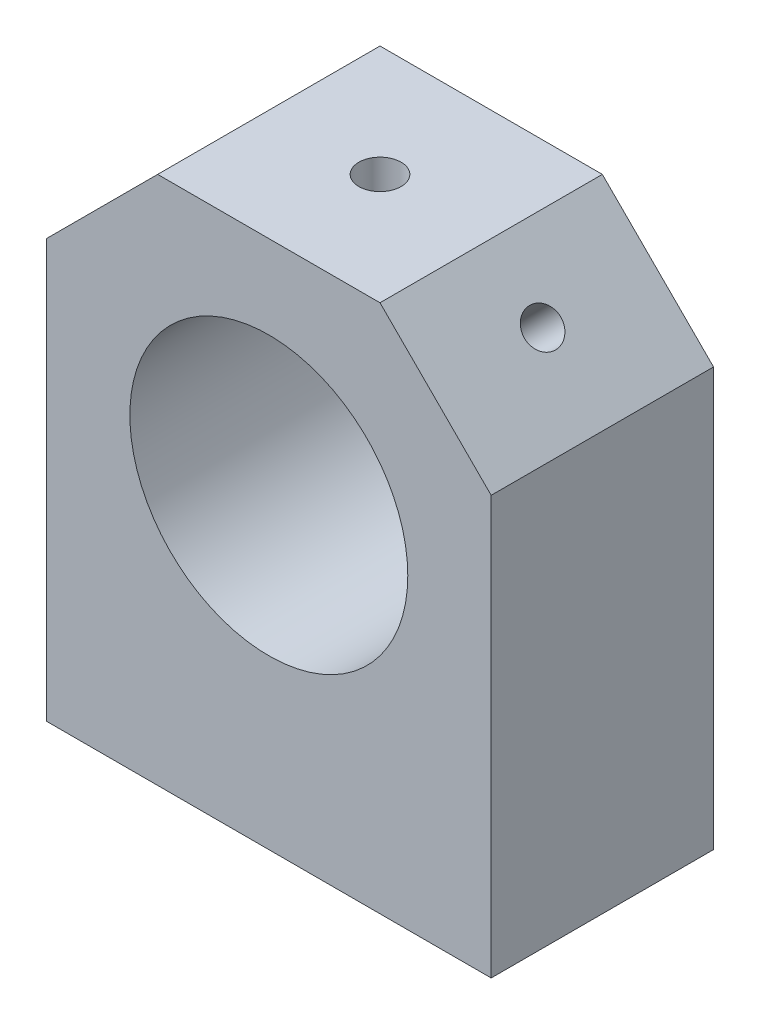
SolidWorks part; units mm, degrees
ref_plane "Front Plane" through (0, 0, 0) normal (0, 0, 1) x (1, 0, 0)
ref_plane "Top Plane" through (0, 0, 0) normal (0, 1, 0) x (1, 0, 0)
ref_plane "Right Plane" through (0, 0, 0) normal (1, 0, 0) x (0, 0, -1)
sketch "Sketch2" plane through (0, 0, 0) normal (0, 0, 1) x (1, 0, 0)
  line L0 (-38.1, 60.452) -> (-50.8, 47.752)
  line L1 (0, 0) -> (-50.8, 0)
  line L2 (0, 0) -> (0, 47.752)
  line L3 (-12.7, 60.452) -> (-38.1, 60.452)
  line L4 (-50.8, 0) -> (-50.8, 47.752)
  line L5 (-12.7, 60.452) -> (0, 47.752)
  circle A0 centre (-25.4, 35.052) radius 15.875
  dimension "D8" = 31.75
  dimension "D1" = 50.8
  dimension "D2" = 60.452
  dimension "D3" = 25.4
  dimension "D4" = 45
  dimension "D5" = 45
  dimension "D6" = 25.4
  dimension "D7" = 35.052
extrude "Boss-Extrude1" add sketch "Sketch2" along normal blind 25.4
sketch "Sketch3" plane through (-49.276, 49.276, 0) normal (-0.7071, 0.7071, 0) x (0, 0, 1)
  line L0 (25.4, 15.8053) -> (0, 15.8053) construction
  line L1 (25.4, 15.8053) -> (25.4, -2.1553) construction
  circle A0 centre (12.7, 6.1533) radius 2.0828
  dimension "D3" = 4.1656
  dimension "D1" = 9.652
  dimension "D2" = 12.7
sketch "Sketch4" plane through (0, 60.452, 0) normal (0, 1, 0) x (1, 0, 0)
  line L0 (-12.7, -25.4) -> (-12.7, 0) construction
  line L1 (-12.7, -25.4) -> (-38.1, -25.4) construction
  circle A0 centre (-25.4, -12.7) radius 2.413
  dimension "D3" = 4.826
  dimension "D1" = 12.7
  dimension "D2" = 12.7
hole_wizard "1/2-20 Tapped Hole1" positions "3DSketch2" profile "Sketch7" tap size "1/2-20" standard "ANSI Inch"
sketch3d "3DSketch2"
  point P0 (-25.4, 60.452, 12.7)
sketch "Sketch7" plane through (-25.4, 60.452, 12.7) normal (1, 0, 0) x (0, 0, 1)
  line L0 (0, 0) -> (0, 33.1999)
  line L1 (0, 33.1999) -> (2.413, 31.75)
  line L2 (2.413, 31.75) -> (2.413, 0)
  line L5 (2.413, 0) -> (0, 0)
  line L10 (0, 33.1999) -> (-2.413, 31.75) construction
  line L11 (0, -6.35) -> (0, 107.95) construction
  dimension "Tap Drill Dia." = 4.826
  dimension "Tap Drill Depth" = 31.75
  dimension "Drill Angle" = 118
cosmetic thread "Hole Thread1" parameters "D1"=25.4, "D2"=12.7
hole_wizard "1/2-20 Tapped Hole2" positions "3DSketch3" profile "Sketch8" tap size "1/2-20" standard "ANSI Inch"
sketch3d "3DSketch3"
  point P0 (-44.925, 53.627, 12.7)
sketch "Sketch8" plane through (-44.925, 53.627, 12.7) normal (0, 0, 1) x (-0.7071, -0.7071, 0)
  line L0 (0, 0) -> (0, 33.0015)
  line L1 (0, 33.0015) -> (2.0828, 31.75)
  line L2 (2.0828, 31.75) -> (2.0828, 0)
  line L5 (2.0828, 0) -> (0, 0)
  line L10 (0, 33.0015) -> (-2.0828, 31.75) construction
  line L11 (0, -6.35) -> (0, 107.95) construction
  dimension "Tap Drill Dia." = 4.1656
  dimension "Tap Drill Depth" = 31.75
  dimension "Drill Angle" = 118
cosmetic thread "Hole Thread2" parameters "D1"=25.4, "D2"=12.7
hole_wizard "1/2-20 Tapped Hole3" positions "3DSketch4" profile "Sketch9" tap size "1/2-20" standard "ANSI Inch"
sketch3d "3DSketch4"
  line L0 (0, 47.752, 25.4) -> (0, 47.752, 0) construction
  line L1 (0, 47.752, 0) -> (-12.7, 60.452, 0) construction
  point P0 (-6.825, 54.577, 12.7)
  point P5 (0, 0, 0)
  dimension "D1" = 9.652
  dimension "D2" = 12.7
sketch "Sketch9" plane through (-6.825, 54.577, 12.7) normal (0, 0, 1) x (-0.7071, 0.7071, 0)
  line L0 (0, 0) -> (0, 33.0015)
  line L1 (0, 33.0015) -> (2.0828, 31.75)
  line L2 (2.0828, 31.75) -> (2.0828, 0)
  line L5 (2.0828, 0) -> (0, 0)
  line L10 (0, 33.0015) -> (-2.0828, 31.75) construction
  line L11 (0, -6.35) -> (0, 107.95) construction
  dimension "Tap Drill Dia." = 4.1656
  dimension "Tap Drill Depth" = 31.75
  dimension "Drill Angle" = 118
cosmetic thread "Hole Thread3" parameters "D1"=25.4, "D2"=12.7
